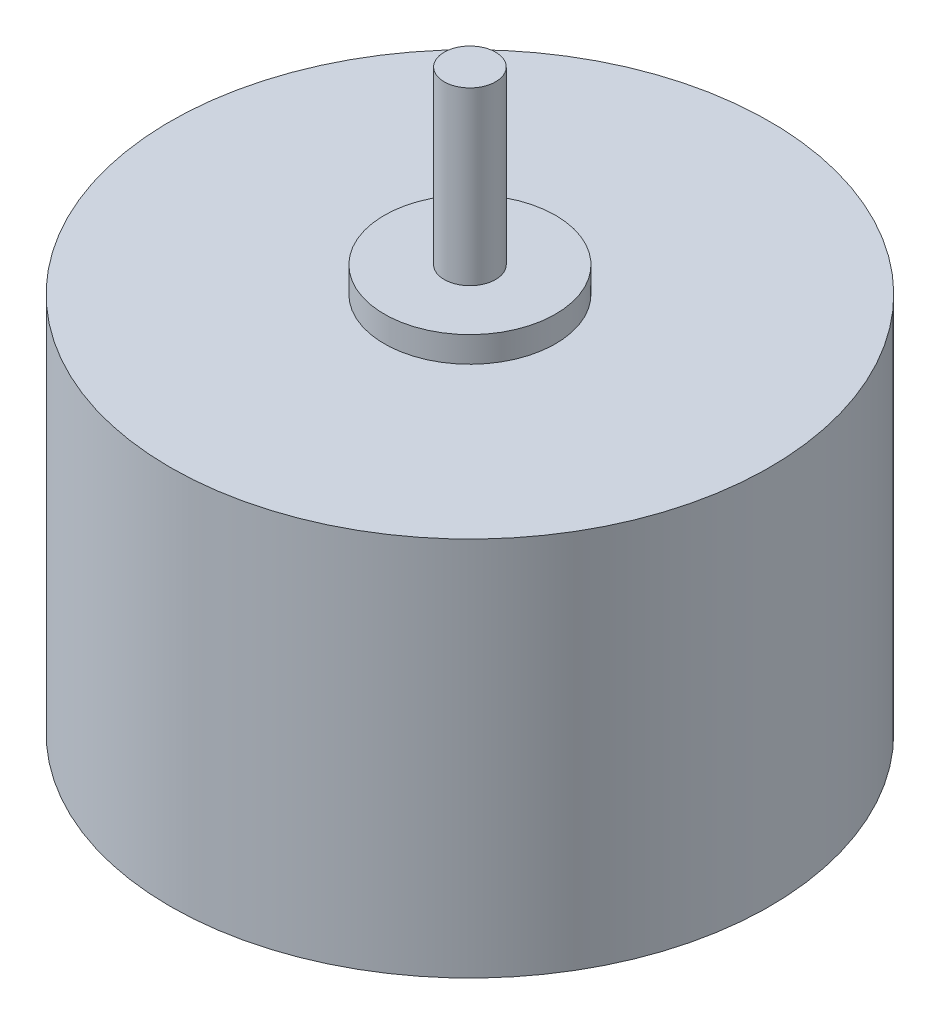
SolidWorks part; units mm, degrees
ref_plane "Front Plane" through (0, 0, 0) normal (0, 0, 1) x (1, 0, 0)
ref_plane "Top Plane" through (0, 0, 0) normal (0, 1, 0) x (1, 0, 0)
ref_plane "Right Plane" through (0, 0, 0) normal (1, 0, 0) x (0, 0, -1)
sketch "Sketch1" plane through (0, 0, 0) normal (0, 1, 0) x (1, 0, 0)
  circle A0 centre (0, 0) radius 17.5
extrude "Boss-Extrude1" add sketch "Sketch1" along normal blind 22.2
sketch "Sketch2" plane through (0, 0, 0) normal (0, 1, 0) x (1, 0, 0)
  circle A0 centre (0, 0) radius 5
extrude "Boss-Extrude2" add sketch "Sketch2" along normal blind 23.7
sketch "Sketch3" plane through (0, 0, 0) normal (0, 1, 0) x (1, 0, 0)
  circle A0 centre (0, 0) radius 1.5
extrude "Boss-Extrude3" add sketch "Sketch3" along normal blind 33.7
